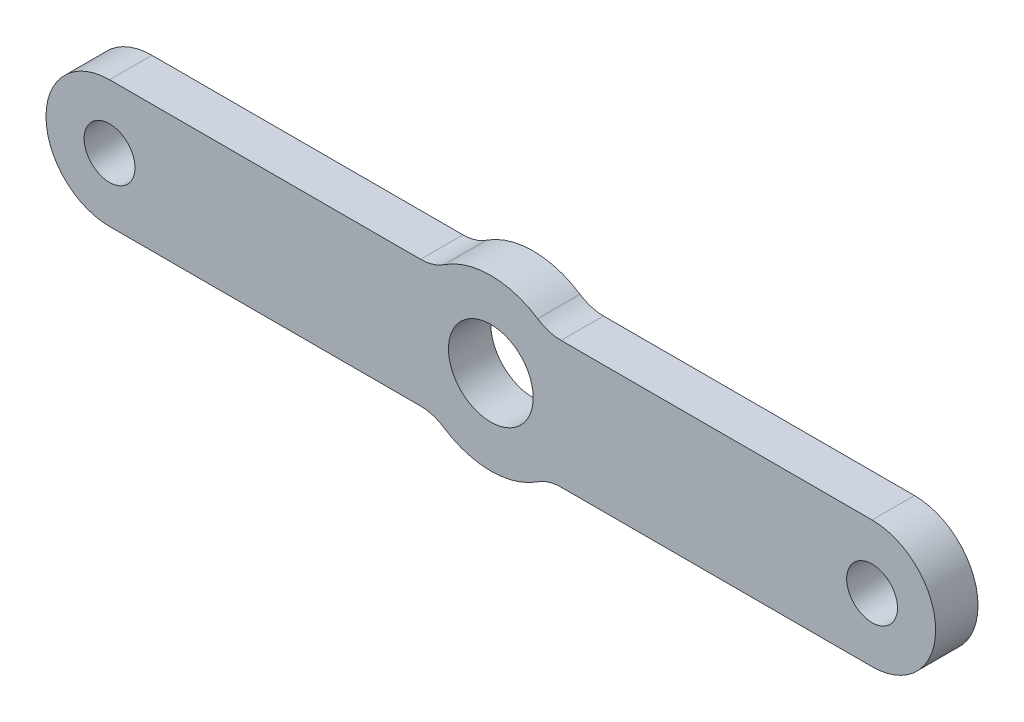
SolidWorks part; units mm, degrees
material "AISI 1020"
ref_plane "Front Plane" through (0, 0, 0) normal (0, 0, 1) x (1, 0, 0)
ref_plane "Top Plane" through (0, 0, 0) normal (0, 1, 0) x (1, 0, 0)
ref_plane "Right Plane" through (0, 0, 0) normal (1, 0, 0) x (0, 0, -1)
sketch "Sketch1" plane through (0, 0, 0) normal (0, 0, 1) x (1, 0, 0)
  line L0 (-57.15, 0) -> (57.15, 0) construction
  line L1 (-57.15, 9.525) -> (-10.5303, 9.525)
  line L2 (-57.15, -9.525) -> (-10.5303, -9.525)
  line L3 (10.5303, 9.525) -> (57.15, 9.525)
  line L4 (10.5303, -9.525) -> (57.15, -9.525)
  circle A0 centre (-57.15, 0) radius 3.81
  circle A1 centre (57.15, 0) radius 3.81
  arc A2 (-57.15, 9.525) -> (-57.15, -9.525) centre (-57.15, 0) ccw
  circle A3 centre (0, 0) radius 6.35
  arc A4 (57.15, -9.525) -> (57.15, 9.525) centre (57.15, 0) ccw
  arc A5 (-7.0202, -10.5833) -> (7.0202, -10.5833) centre (0, 0) ccw
  arc A6 (7.0202, 10.5833) -> (-7.0202, 10.5833) centre (0, 0) ccw
  arc A7 (-10.5303, 9.525) -> (-7.0202, 10.5833) centre (-10.5303, 15.875) ccw
  arc A8 (7.0202, 10.5833) -> (10.5303, 9.525) centre (10.5303, 15.875) ccw
  arc A9 (7.0202, -10.5833) -> (10.5303, -9.525) centre (10.5303, -15.875) cw
  arc A10 (-7.0202, -10.5833) -> (-10.5303, -9.525) centre (-10.5303, -15.875) ccw
  point P14 (0, 0)
  point P20 (8.4003, 9.525)
  point P23 (8.4003, -9.525)
  dimension "D2" = 7.62
  dimension "D3" = 12.7
  dimension "D4" = 19.05
  dimension "D5" = 25.4
  dimension "D6" = 6.35
  dimension "D1" = 114.3
extrude "Boss-Extrude1" add sketch "Sketch1" along normal blind 6.35
